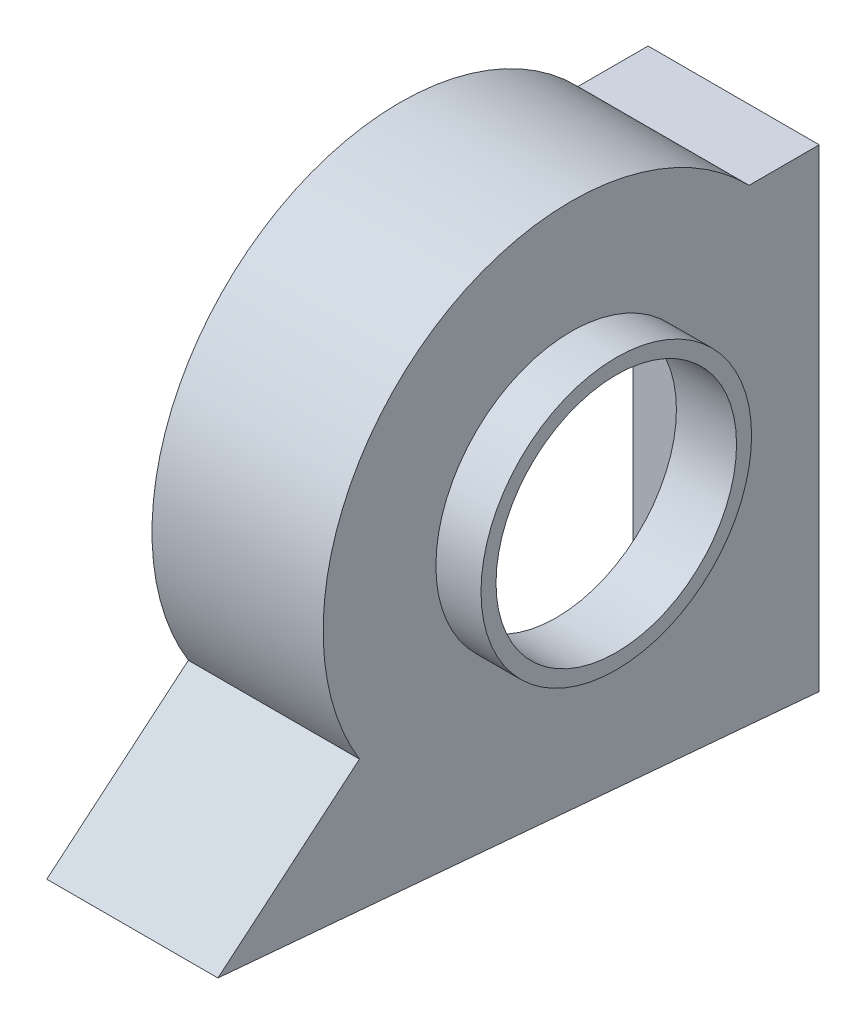
SolidWorks part; units mm, degrees
ref_plane "Front Plane" through (0, 0, 0) normal (0, 0, 1) x (1, 0, 0)
ref_plane "Top Plane" through (0, 0, 0) normal (0, 1, 0) x (1, 0, 0)
ref_plane "Right Plane" through (0, 0, 0) normal (1, 0, 0) x (0, 0, -1)
sketch "Sketch1" plane through (0, 0, 0) normal (0, 1, 0) x (1, 0, 0)
  line L1 (-5.6925, -20) -> (5.6925, -20)
  line L2 (-5.6925, -20) -> (-5.6925, 20)
  line L3 (-5.6925, 20) -> (5.6925, 20)
  line L4 (5.6925, -20) -> (5.6925, 20)
  line L5 (-5.6925, -20) -> (5.6925, 20) construction
  line L6 (-5.6925, 20) -> (5.6925, -20) construction
  point P0 (0, 0)
  dimension "D1" = 40
  dimension "D2" = 11.385
extrude "Boss-Extrude1" add sketch "Sketch1" along normal blind 35
sketch "Sketch6" plane through (5.6925, 0, 0) normal (1, 0, 0) x (0, 0, -1)
  line L0 (20, 35) -> (20, 0) construction
  line L1 (-20, 0) -> (20, 0) construction
  line L5 (-10.5828, 7.902) -> (-20, 0)
  line L7 (20, 28) -> (20, 35)
  line L8 (20, 35) -> (-20, 35)
  line L9 (-20, 35) -> (-20, 0)
  line L10 (-20, 0) -> (20, 0)
  line L11 (15.3322, 28) -> (20, 28)
  line L12 (20, 28) -> (20, 0)
  arc A0 (15.3322, 28) -> (-10.5828, 7.902) centre (3.5, 16.5) ccw
  point P1 (20, 27.0125)
  dimension "D1" = 33
  dimension "D2" = 28
  dimension "D3" = 50
extrude "Cut-Extrude3" cut sketch "Sketch6" against normal through all
sketch "Sketch2" plane through (5.6925, 0, 0) normal (1, 0, 0) x (0, 0, -1)
  circle A0 centre (3.5, 16.5) radius 9
  circle A1 centre (3.5, 16.5) radius 8.8106 construction
  dimension "D2" = 18
extrude "Boss-Extrude2" add sketch "Sketch2" along normal blind 3
sketch "Sketch7" plane through (0, 0, 0) normal (0, -1, 0) x (1, 0, 0)
  line L1 (-5.6925, 20) -> (5.6925, 20)
  line L2 (-5.6925, 20) -> (-5.6925, -20)
  line L3 (-5.6925, -20) -> (5.6925, -20)
  line L4 (5.6925, 20) -> (5.6925, -20)
extrude "Boss-Extrude3" add sketch "Sketch7" along normal blind 6
sketch "Sketch8" plane through (5.6925, 0, 0) normal (1, 0, 0) x (0, 0, -1)
  line L0 (-20, 0) -> (20, -3.4995)
  line L1 (20, 28) -> (20, -6) construction
  line L2 (20, -6) -> (-20, -6) construction
  line L3 (-20, 0) -> (-20, -6)
  line L4 (-20, -6) -> (20, -6)
  line L5 (20, -6) -> (20, -3.4995)
  dimension "D1" = 5
extrude "Cut-Extrude4" cut sketch "Sketch8" against normal through all
shell "Shell1" thickness 1
sketch "Sketch4" plane through (7.6925, 0, 0) normal (-1, 0, 0) x (0, 0, 1)
  circle A0 centre (-3.5, 16.5) radius 8
extrude "Cut-Extrude2" cut sketch "Sketch4" against normal blind 6
sketch "Sketch9" plane through (0, 0, -20) normal (0, 0, -1) x (-1, 0, 0)
  line L0 (-8.6925, 16.5) -> (10.2337, 16.5) construction
  line L1 (-8.6925, 25.5) -> (-8.6925, 7.5) construction
  line L3 (5.6925, 28) -> (5.6925, -3.4995) construction
  circle A1 centre (5.6925, 16.5) radius 3
  dimension "D1" = 6
extrude "Cut-Extrude5" cut sketch "Sketch9" against normal blind 7
